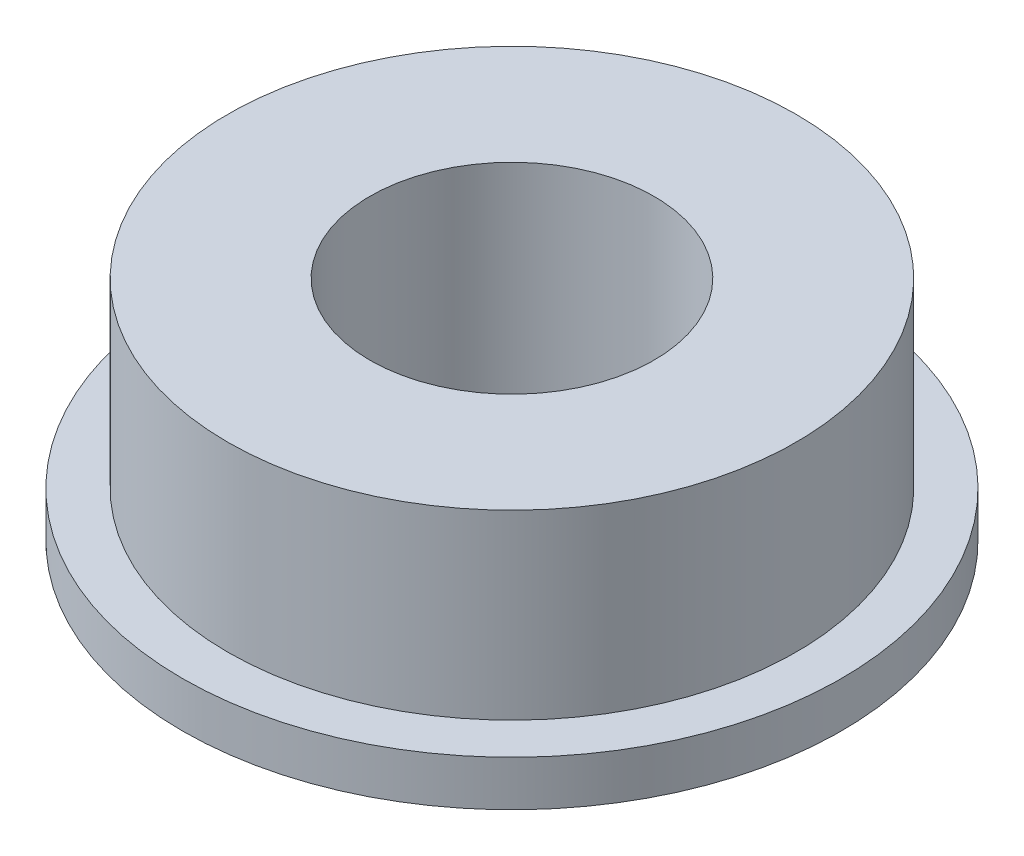
SolidWorks part; units mm, degrees
ref_plane "前视基准面" through (0, 0, 0) normal (0, 0, 1) x (1, 0, 0)
ref_plane "上视基准面" through (0, 0, 0) normal (0, 1, 0) x (1, 0, 0)
ref_plane "右视基准面" through (0, 0, 0) normal (1, 0, 0) x (0, 0, -1)
sketch "草图1" plane through (0, 0, 0) normal (0, 1, 0) x (1, 0, 0)
  circle A0 centre (0, 0) radius 5.8
  dimension "D1" = 11.6
extrude "凸台-拉伸1" add sketch "草图1" along normal blind 0.8
sketch "草图2" plane through (0, 0.8, 0) normal (0, 1, 0) x (1, 0, 0)
  circle A0 centre (0, 0) radius 5
  dimension "D1" = 10
extrude "凸台-拉伸2" add sketch "草图2" along normal blind 3.2
sketch "草图3" plane through (0, 4, 0) normal (0, 1, 0) x (1, 0, 0)
  point P0 (0, 0)
hole_wizard "孔1" positions "草图3" profile "草图4" legacy end condition up to next
sketch "草图4" plane through (0, 4, 0) normal (1, 0, 0) x (0, 0, 1)
  line L0 (0, 0) -> (0, 4)
  line L1 (0, 4) -> (2.5, 4)
  line L2 (2.5, 4) -> (2.5, 0)
  line L3 (2.5, 0) -> (0, 0)
  line L4 (0, 110) -> (0, -10) construction
  dimension "直径" = 5
  dimension "深度" = 4
